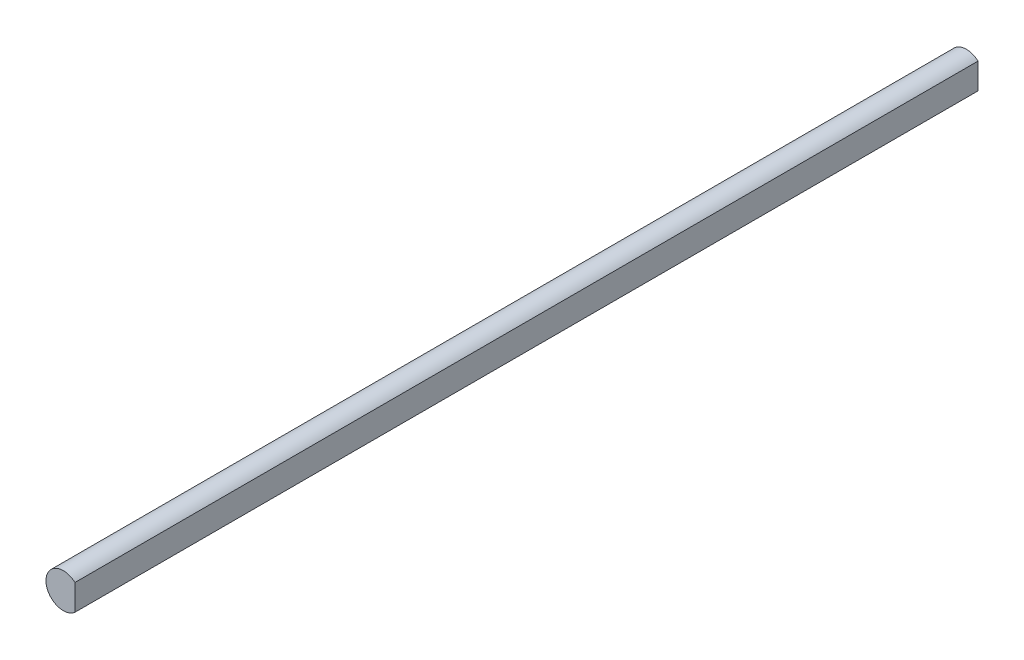
SolidWorks part; units mm, degrees
ref_plane "Alzado" through (0, 0, 0) normal (0, 0, 1) x (1, 0, 0)
ref_plane "Planta" through (0, 0, 0) normal (0, 1, 0) x (1, 0, 0)
ref_plane "Vista lateral" through (0, 0, 0) normal (1, 0, 0) x (0, 0, -1)
sketch "Croquis1" plane through (0, 0, 0) normal (0, 0, 1) x (1, 0, 0)
  circle A0 centre (0, 0) radius 2.5
  dimension "D1" = 5
extrude "Saliente-Extruir1" add sketch "Croquis1" along normal blind 130
sketch "Croquis2" plane through (0, 0, 0) normal (0, 0, -1) x (-1, 0, 0)
  line L0 (-1.6729, 1.8578) -> (-1.6729, -1.8578)
  arc A0 (-1.6729, 1.8578) -> (-1.6729, -1.8578) centre (0, 0) ccw
extrude "Cortar-Extruir1" cut sketch "Croquis2" against normal through all
